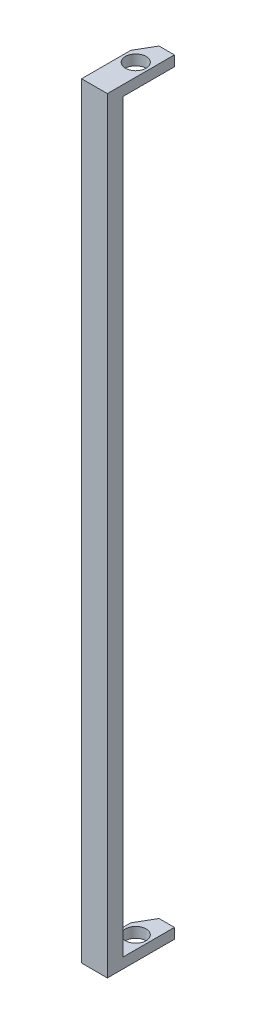
SolidWorks part; units mm, degrees
ref_plane "Plan de face" through (0, 0, 0) normal (0, 0, 1) x (1, 0, 0)
ref_plane "Plan de dessus" through (0, 0, 0) normal (0, 1, 0) x (1, 0, 0)
ref_plane "Plan de droite" through (0, 0, 0) normal (1, 0, 0) x (0, 0, -1)
sketch "Esquisse1" plane through (0, 0, 0) normal (0, 1, 0) x (1, 0, 0)
  line L0 (2.01, 10) -> (0, 6.52)
  line L2 (0, 0) -> (0, 6.52)
  line L3 (2.01, 10) -> (5, 10)
  line L4 (5, 0) -> (5, 10)
  line L8 (0, 0) -> (0, -3)
  line L9 (0, -3) -> (5, -3)
  line L10 (5, 0) -> (5, -3)
  circle A0 centre (2.5, 5) radius 2
  dimension "D5" = 3
  dimension "D1" = 5
  dimension "D2" = 10
  dimension "D3" = 2.99
  dimension "D4" = 6.52
extrude "Boss.-Extru.1" add sketch "Esquisse1" along normal blind 2
sketch "Esquisse2" plane through (0, 2, 0) normal (0, 1, 0) x (1, 0, 0)
  line L0 (5, -3) -> (5, 10) construction
  line L1 (0, -3) -> (5, -3)
  line L2 (0, -3) -> (0, 0)
  line L3 (0, 0) -> (5, 0)
  line L4 (5, -3) -> (5, 0)
  dimension "D1" = 3
extrude "Boss.-Extru.2" add sketch "Esquisse2" along normal blind 144.52
sketch "Esquisse3" plane through (0, 146.52, 0) normal (0, 1, 0) x (1, 0, 0)
  line L0 (2.01, 10) -> (0, 6.52)
  line L1 (0, -3) -> (5, -3)
  line L2 (0, -3) -> (0, 6.52)
  line L3 (2.01, 10) -> (5, 10)
  line L4 (5, -3) -> (5, 10)
  circle A0 centre (2.5, 5) radius 2
extrude "Boss.-Extru.3" add sketch "Esquisse3" along normal blind 2
